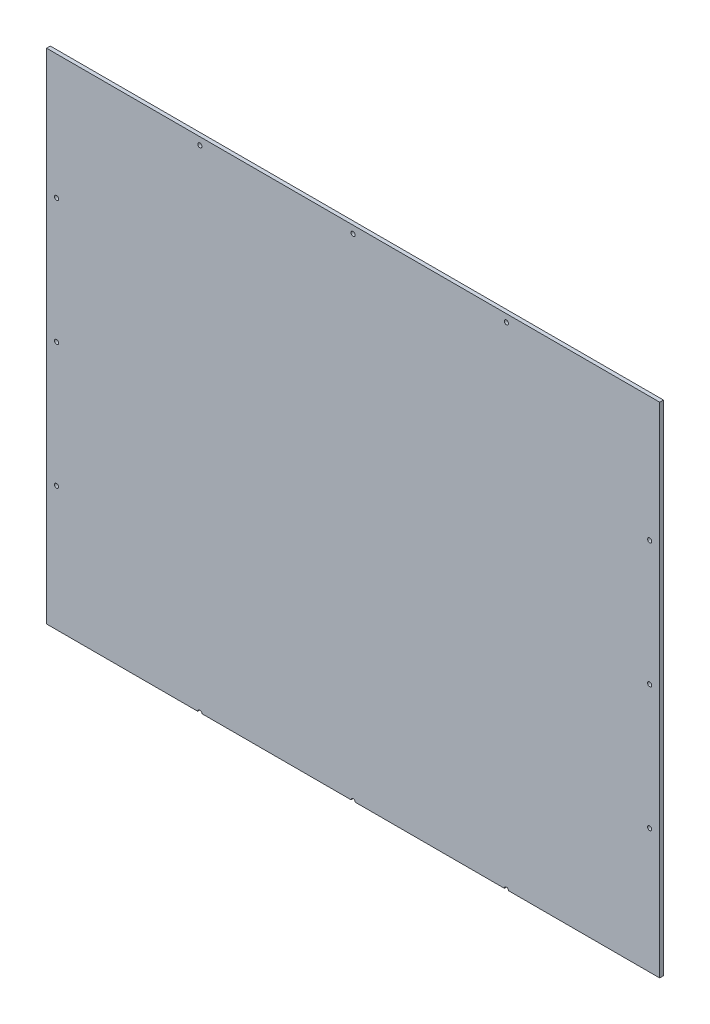
SolidWorks part; units mm, degrees
ref_plane "Front Plane" through (0, 0, 0) normal (0, 0, 1) x (1, 0, 0)
ref_plane "Top Plane" through (0, 0, 0) normal (0, 1, 0) x (1, 0, 0)
ref_plane "Right Plane" through (0, 0, 0) normal (1, 0, 0) x (0, 0, -1)
sketch "Sketch1" plane through (0, 0, 0) normal (0, 0, 1) x (1, 0, 0)
  line L1 (-367, 298.4953) -> (367, 298.4953)
  line L2 (-367, 298.4953) -> (-367, -298.5047)
  line L3 (-367, -298.5047) -> (367, -298.5047)
  line L4 (367, 298.4953) -> (367, -298.5047)
  point P4 (362.7938, -298.5047)
  point P9 (0, 0)
  point P10 (0, 0)
  point P11 (0, 0)
  point P15 (0, 0)
  point P16 (0, 0)
  dimension "D1" = 597
  dimension "D2" = 734
  dimension "D4" = 367
extrude "Boss-Extrude1" add sketch "Sketch1" along normal blind 4.5 contours L1 L4 L3 L2
sketch "Sketch2" plane through (0, 0, 4.5) normal (0, 0, 1) x (1, 0, 0)
  line L0 (-367, 298.4953) -> (-367, -298.5047) construction
  line L1 (367, -0.0047) -> (0, 0) construction
  line L2 (367, 298.4953) -> (367, -298.5047) construction
  line L3 (0, 0) -> (-367, -0.0047) construction
  line L4 (0, -298.4499) -> (0, 0) construction
  line L5 (0, 0) -> (0, 298.4953) construction
  line L6 (-367, 298.4953) -> (367, 298.4953) construction
  line L7 (0, -298.4499) -> (183.5, -298.4499) construction
  line L8 (0, -298.4499) -> (-183.5, -298.4499) construction
  circle A0 centre (-355, -149.2545) radius 2.5
  circle A1 centre (-355, -0.0045) radius 2.5
  circle A2 centre (-355, 149.2455) radius 2.5
  circle A3 centre (355, -149.2545) radius 2.5
  circle A4 centre (355, -0.0045) radius 2.5
  circle A5 centre (355, 149.2455) radius 2.5
  circle A6 centre (0, 289.4953) radius 2.5
  circle A7 centre (183.5, 289.4953) radius 2.5
  circle A8 centre (-183.5, 289.4953) radius 2.5
  circle A9 centre (0, -298.4499) radius 2.5
  circle A10 centre (183.5, -298.4499) radius 2.5
  circle A11 centre (-183.5, -298.4499) radius 2.5
  dimension "D1" = 12
  dimension "D4" = 9
  dimension "D7" = 2
  dimension "D2" = 149.25
  dimension "D8" = 183.5
  dimension "D10" = 183.5
  dimension "D3" = 3
  dimension "D5" = 2
  dimension "D6" = 2
  dimension "D9" = 2
extrude "Cut-Extrude1" cut sketch "Sketch2" against normal blind 10
